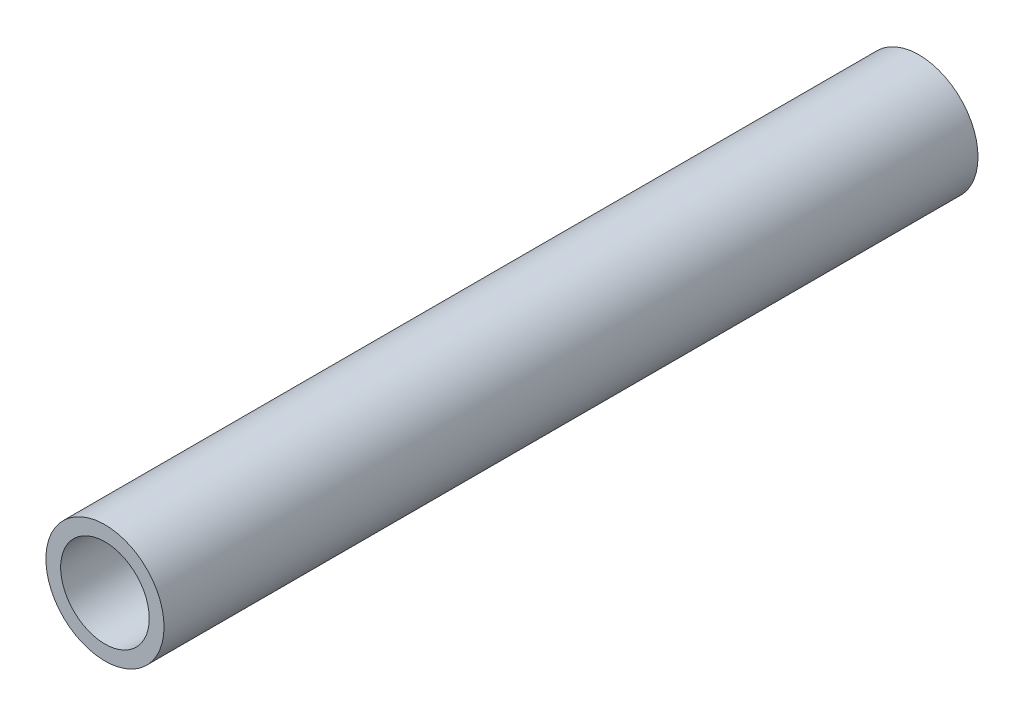
SolidWorks part; units mm, degrees
ref_plane "Front Plane" through (0, 0, 0) normal (0, 0, 1) x (1, 0, 0)
ref_plane "Top Plane" through (0, 0, 0) normal (0, 1, 0) x (1, 0, 0)
ref_plane "Right Plane" through (0, 0, 0) normal (1, 0, 0) x (0, 0, -1)
sketch "Sketch1" plane through (0, 0, 0) normal (0, 0, 1) x (1, 0, 0)
  circle A0 centre (0, 0) radius 0.508
  circle A1 centre (0, 0) radius 0.381
  dimension "D1" = 0.762
  dimension "D2" = 1.016
extrude "Boss-Extrude1" add sketch "Sketch1" along normal blind 7
